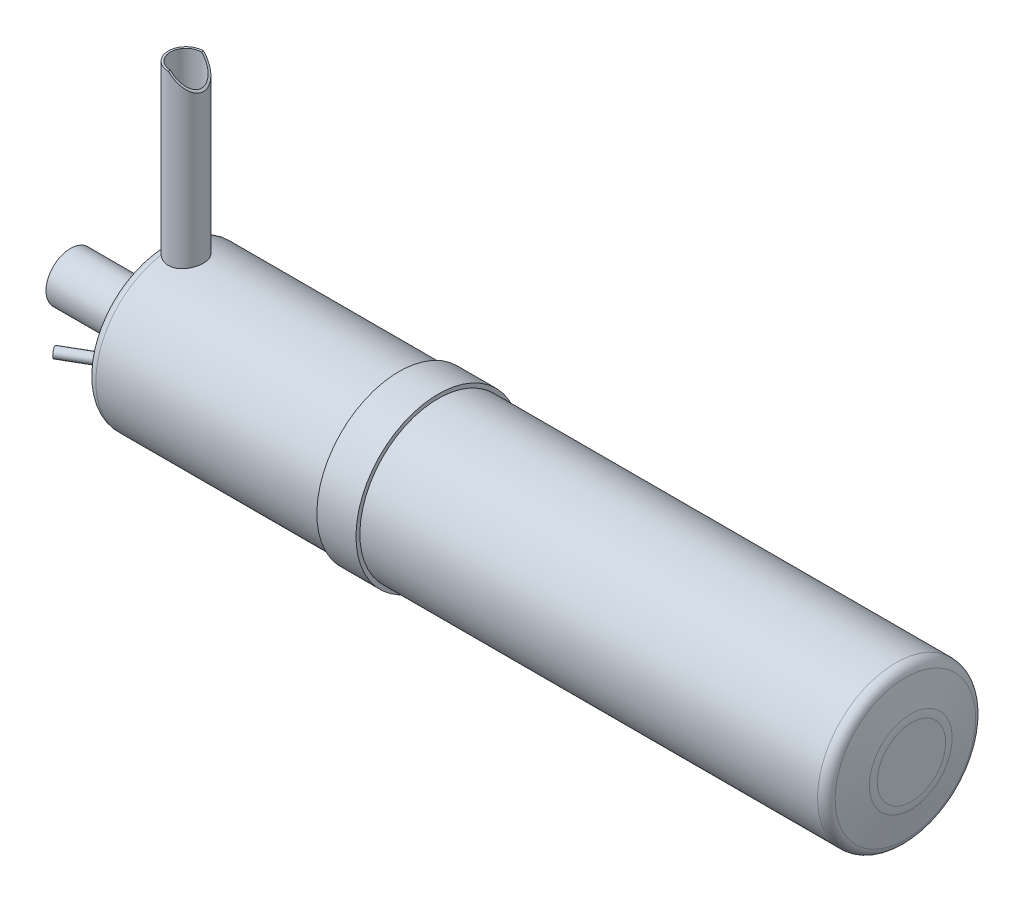
SolidWorks part; units mm, degrees
ref_plane "Front Plane" through (0, 0, 0) normal (0, 0, 1) x (1, 0, 0)
ref_plane "Top Plane" through (0, 0, 0) normal (0, 1, 0) x (1, 0, 0)
ref_plane "Right Plane" through (0, 0, 0) normal (1, 0, 0) x (0, 0, -1)
sketch "Sketch1" plane through (0, 0, 0) normal (0, 0, 1) x (1, 0, 0)
  line L0 (0, 0) -> (428, 0) construction
  line L1 (0, 12.5) -> (45, 12.5)
  line L2 (45, 12.5) -> (45, 15.8371)
  line L3 (45.2746, 19.1401) -> (48.0687, 35.8258)
  line L4 (53, 40) -> (168, 40)
  line L5 (168, 40) -> (168, 42)
  line L6 (168, 42) -> (188, 42)
  line L7 (188, 42) -> (188, 40)
  line L8 (188, 40) -> (422, 40)
  line L9 (426.9156, 35.915) -> (429.6622, 21.1602)
  line L10 (430, 17.5) -> (430, 0)
  line L11 (0, 12.5) -> (0, 10.5)
  line L12 (0, 10.5) -> (47, 10.5)
  line L13 (47, 10.5) -> (47, 15.8371)
  line L14 (430, 0) -> (428, 0)
  line L15 (428, 0) -> (428, 17.5)
  line L16 (47.2472, 18.8098) -> (50.0412, 35.4955)
  line L17 (53, 38) -> (422, 38)
  line L18 (427.696, 20.7942) -> (424.9493, 35.549)
  arc A0 (48.0687, 35.8258) -> (53, 40) centre (53, 35) cw
  arc A1 (422, 40) -> (426.9156, 35.915) centre (422, 35) cw
  arc A2 (45, 15.8371) -> (45.2746, 19.1401) centre (65, 15.8371) cw
  arc A3 (429.6622, 21.1602) -> (430, 17.5) centre (410, 17.5) cw
  arc A4 (47, 15.8371) -> (47.2472, 18.8098) centre (65, 15.8371) cw
  arc A5 (50.0412, 35.4955) -> (53, 38) centre (53, 35) cw
  arc A6 (428, 17.5) -> (427.696, 20.7942) centre (410, 17.5) ccw
  arc A7 (424.9493, 35.549) -> (422, 38) centre (422, 35) ccw
  point P23 (45, 17.5)
  dimension "D3" = 5
  dimension "D7" = 20
  dimension "D9" = 5
  dimension "D10" = 20
  dimension "D1" = 25
  dimension "D2" = 80
  dimension "D4" = 21
  dimension "D5" = 45
  dimension "D6" = 35
  dimension "D8" = 8
  dimension "D11" = 35
  dimension "D12" = 8
  dimension "D13" = 2
  dimension "D14" = 115
  dimension "D15" = 20
  dimension "D16" = 2
  dimension "D17" = 385
  dimension "D18" = 2
revolve "Revolve1" add sketch "Sketch1" angle 360 about L0
sketch "Sketch2" plane through (0, 0, 0) normal (0, 0, 1) x (1, 0, 0)
  line L0 (59.0687, 37) -> (59.0687, 125) construction
  line L1 (50.0687, 125) -> (50.0687, 37)
  line L2 (50.0687, 37) -> (51.0687, 37)
  line L3 (51.0687, 37) -> (51.0687, 125)
  line L4 (51.0687, 125) -> (50.0687, 125)
  line L6 (48.0687, -35.8258) -> (48.0687, 35.8258) construction
  line L7 (168, 40) -> (53, 40) construction
  line L8 (59.0687, 125) -> (51.0687, 125) construction
  line L9 (51.0687, 37) -> (59.0687, 37) construction
  dimension "D1" = 1
  dimension "D2" = 18
  dimension "D3" = 2
  dimension "D4" = 3
  dimension "D5" = 85
revolve "Revolve2" add sketch "Sketch2" angle 360 about L0
sketch "Sketch3" plane through (0, 0, 0) normal (0, 0, 1) x (1, 0, 0)
  line L0 (59.0687, 125) -> (68.0687, 125)
  line L1 (68.0687, 125) -> (50.0687, 125) construction
  line L2 (68.0687, 125) -> (68.0687, 116)
  line L3 (68.0687, 40) -> (68.0687, 125) construction
  line L4 (68.0687, 116) -> (59.0687, 125)
extrude "Cut-Extrude1" cut sketch "Sketch3" against normal mid plane 20
sketch "Sketch4" plane through (0, 0, 0) normal (0, 1, 0) x (1, 0, 0)
  line L0 (29.3511, -37.4829) -> (46.6716, -27.4829) construction
  line L1 (45.2746, -19.1401) -> (48.0687, -35.8258) construction
  line L2 (0, -12.5) -> (45, -12.5) construction
  line L3 (49.1537, -27.782) -> (30.1011, -38.782)
  line L4 (30.1011, -38.782) -> (30.6011, -39.648)
  line L5 (30.6011, -39.648) -> (49.6537, -28.648)
  line L6 (49.6537, -28.648) -> (49.1537, -27.782)
  line L7 (29.3511, -37.4829) -> (30.1011, -38.782) construction
  dimension "D1" = 30
  dimension "D2" = 1
  dimension "D3" = 5
  dimension "D4" = 20
  dimension "D5" = 22
revolve "Revolve3" add sketch "Sketch4" angle 360 about L0
